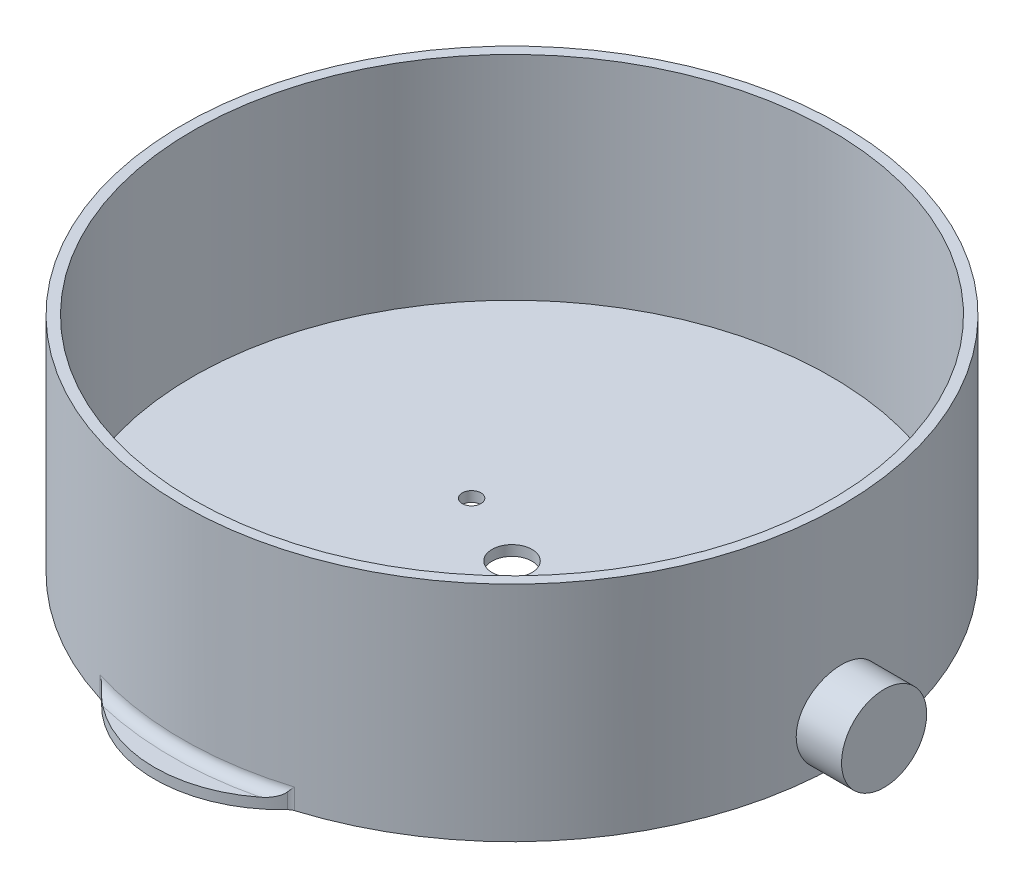
SolidWorks part; units mm, degrees
ref_plane "Front Plane" through (0, 0, 0) normal (0, 0, 1) x (1, 0, 0)
ref_plane "Top Plane" through (0, 0, 0) normal (0, 1, 0) x (1, 0, 0)
ref_plane "Right Plane" through (0, 0, 0) normal (1, 0, 0) x (0, 0, -1)
sketch "Sketch1" plane through (0, 0, 0) normal (0, 1, 0) x (1, 0, 0)
  circle A0 centre (0, 0) radius 75
  dimension "D1" = 150
extrude "Boss-Extrude1" add sketch "Sketch1" along normal blind 50
shell "Shell1" thickness 2.4
sketch "Sketch2" plane through (0, 0, 0) normal (0, 1, 0) x (1, 0, 0)
  line L1 (0, -75) -> (0, -54) construction
  circle A0 centre (0, 0) radius 75 construction
  circle A1 centre (0, -54) radius 21
  circle A2 centre (0, -27.5) radius 1.75
  circle A3 centre (22.9497, -67.25) radius 1.75
  circle A4 centre (-22.9497, -67.25) radius 1.75
  point P17 (0, -54)
  dimension "D1" = 21
  dimension "D2" = 42
  dimension "D3" = 3.5
  dimension "D4" = 26.5
  dimension "D5" = 3
extrude "Cut-Extrude1" cut sketch "Sketch2" against normal through all
sketch "Sketch3" plane through (0, 0, 0) normal (0, 1, 0) x (1, 0, 0)
  arc A0 (-24.8885, -70.75) -> (24.8885, -70.75) centre (0, -54) ccw
  arc A1 (-24.8885, -70.75) -> (24.8885, -70.75) centre (0, 0) ccw
  circle A2 centre (0, 0) radius 75 construction
  dimension "D1" = 60
extrude "Boss-Extrude3" add sketch "Sketch3" against normal blind 2.4
fillet "Fillet1" radius 2.4 3 edges at (0, 0, 77.4) (-22.2377, -1.2, 74.1367) (22.2377, -1.2, 74.1367)
ref_plane "Plane1" through (75, 0, 0) normal (1, 0, 0) x (0, 0, -1)
sketch "Sketch5" plane through (75, 0, 0) normal (1, 0, 0) x (0, 0, -1)
  line L0 (0, 0) -> (0, -2.4) construction
  line L1 (-73.9503, -2.4) -> (77.4, -2.4) construction
  circle A0 centre (0, 7.6) radius 10
  dimension "D2" = 20
  dimension "D1" = 10
extrude "Boss-Extrude5" add sketch "Sketch5" along normal blind 12.4
mirror "Mirror1" about plane through (0, 0, 0) normal (1, 0, 0) of "Boss-Extrude5"
sketch "Sketch6" plane through (0, 0, 0) normal (0, 1, 0) x (1, 0, 0)
  line L0 (0, 8) -> (24.5564, 8) construction
  line L1 (0, 0) -> (0, 8) construction
  circle A0 centre (0, 0) radius 4.7
  circle A1 centre (17.5, 8) radius 2.2
  circle A2 centre (-17.5, 8) radius 2.2
  dimension "D1" = 9.4
  dimension "D3" = 4.4
  dimension "D2" = 8
extrude "Cut-Extrude2" cut sketch "Sketch6" against normal through all
